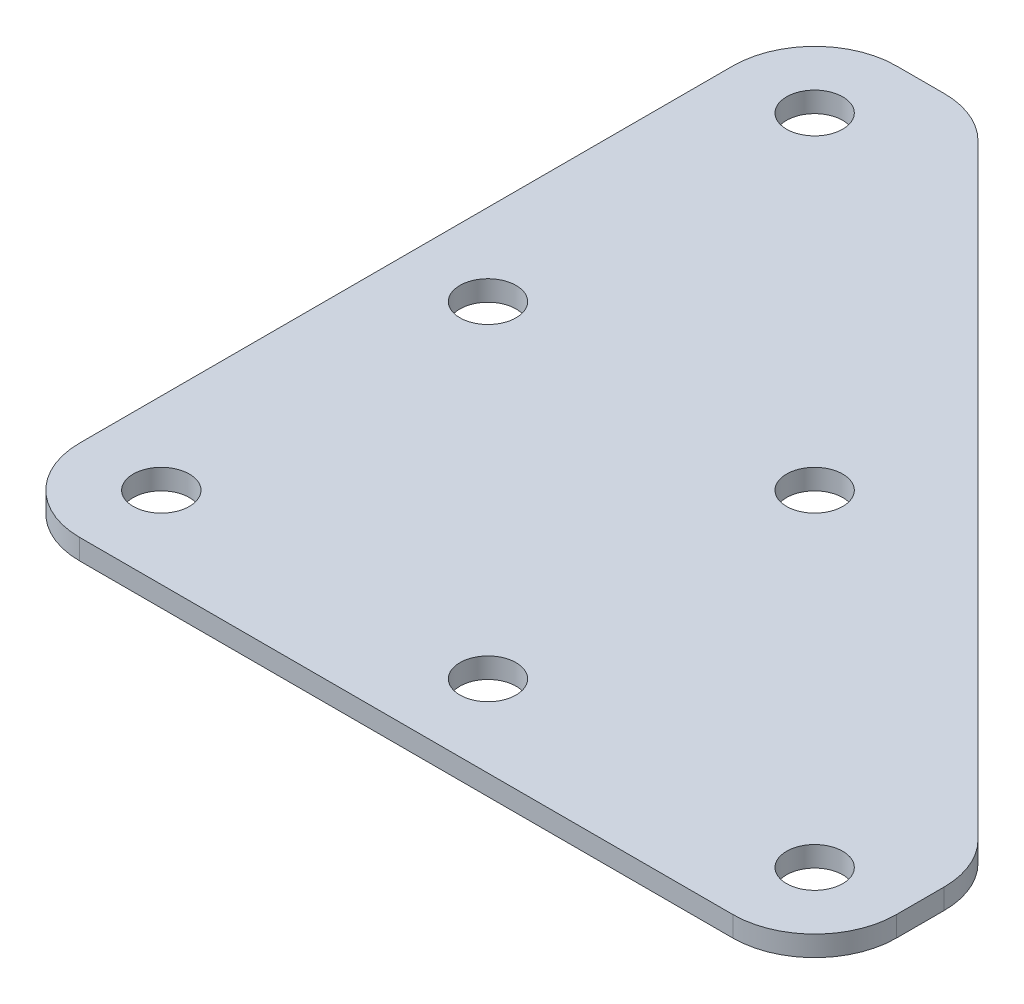
SolidWorks part; units mm, degrees
ref_plane "Front Plane" through (0, 0, 0) normal (0, 0, 1) x (1, 0, 0)
ref_plane "Top Plane" through (0, 0, 0) normal (0, 1, 0) x (1, 0, 0)
ref_plane "Right Plane" through (0, 0, 0) normal (1, 0, 0) x (0, 0, -1)
sketch "Sketch1" plane through (0, 0, 0) normal (0, 1, 0) x (1, 0, 0)
  line L0 (-6.35, 0) -> (-6.35, 50.8)
  line L1 (0, 57.15) -> (3.7197, 57.15)
  line L2 (8.2099, 55.2901) -> (55.2901, 8.2099)
  line L3 (57.15, 3.7197) -> (57.15, 0)
  line L4 (50.8, -6.35) -> (0, -6.35)
  circle A0 centre (0, 0) radius 2.1828
  circle A1 centre (0, 50.8) radius 2.1828
  circle A2 centre (50.8, 0) radius 2.1828
  circle A3 centre (25.4, 0) radius 2.1828
  circle A4 centre (0, 25.4) radius 2.1828
  arc A5 (57.15, 0) -> (50.8, -6.35) centre (50.8, 0) cw
  arc A6 (55.2901, 8.2099) -> (57.15, 3.7197) centre (50.8, 3.7197) cw
  arc A7 (3.7197, 57.15) -> (8.2099, 55.2901) centre (3.7197, 50.8) cw
  arc A8 (-6.35, 50.8) -> (0, 57.15) centre (0, 50.8) cw
  arc A9 (-6.35, 0) -> (0, -6.35) centre (0, 0) ccw
  circle A10 centre (25.4, 25.4) radius 2.1828
  point P18 (57.15, -6.35)
  point P21 (57.15, 6.35)
  point P24 (6.35, 57.15)
  point P27 (-6.35, 57.15)
  point P32 (0, 0)
  point P33 (0, 0)
  point P34 (0, 0)
  point P35 (3.7197, 50.8)
  dimension "D3" = 4.3656
  dimension "D4" = 4.3656
  dimension "D5" = 4.3656
  dimension "D8" = 4.3656
  dimension "D9" = 4.3656
  dimension "D16" = 6.35
  dimension "D17" = 4.3656
  dimension "D1" = 50.8
  dimension "D2" = 50.8
  dimension "D6" = 25.4
  dimension "D7" = 25.4
  dimension "D10" = 6.35
  dimension "D11" = 6.35
  dimension "D12" = 6.35
  dimension "D13" = 6.35
  dimension "D14" = 12.7
  dimension "D15" = 12.7
extrude "Boss-Extrude1" add sketch "Sketch1" along normal mid plane 1.5875
